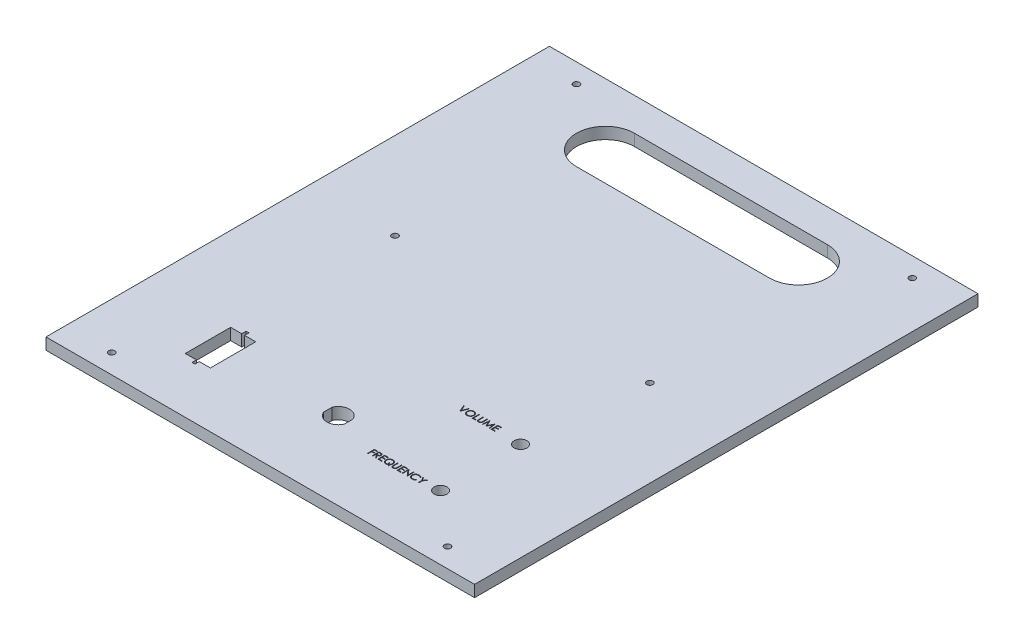
SolidWorks part; units mm, degrees
ref_plane "Front Plane" through (0, 0, 0) normal (0, 0, 1) x (1, 0, 0)
ref_plane "Top Plane" through (0, 0, 0) normal (0, 1, 0) x (1, 0, 0)
ref_plane "Right Plane" through (0, 0, 0) normal (1, 0, 0) x (0, 0, -1)
sketch "Sketch1" plane through (0, 0, 0) normal (0, 1, 0) x (1, 0, 0)
  line L0 (-111, 125.6127) -> (111, 125.6127)
  line L1 (-111, 125.6127) -> (-111, -125.6127)
  line L3 (111, 125.6127) -> (111, -125.6127)
  line L4 (-111, 125.6127) -> (111, -125.6127) construction
  line L5 (-111, -125.6127) -> (111, 125.6127) construction
  line L8 (-111, -125.6127) -> (-111, -165.6127)
  line L9 (-111, -165.6127) -> (111, -165.6127)
  line L10 (111, -125.6127) -> (111, -165.6127)
  point P10 (0, 0)
  dimension "D1" = 222
  dimension "D2" = 40
extrude "Boss-Extrude1" add sketch "Sketch1" along normal blind 6
sketch "Sketch2" plane through (0, 6, 0) normal (0, 1, 0) x (1, 0, 0)
  circle A0 centre (-57, 100.5142) radius 1.6
sketch "Sketch3" plane through (0, 0, 0) normal (0, -1, 0) x (1, 0, 0)
  line L0 (-111, -125.6127) -> (-111, 165.6127) construction
  line L1 (111, -125.6127) -> (-111, -125.6127)
  line L2 (111, -125.6127) -> (111, -95.1873)
  line L3 (111, -95.1873) -> (-111, -95.1873)
  line L4 (-111, -125.6127) -> (-111, -95.1873)
  circle A0 centre (-66, 29.8127) radius 1.6
  circle A1 centre (66, 29.8127) radius 1.6
  dimension "D1" = 3.2
extrude "Cut-Extrude1" cut sketch "Sketch3" against normal blind 10
sketch "Sketch4" plane through (0, 0, 0) normal (0, -1, 0) x (1, 0, 0)
  circle A0 centre (87, 155.6127) radius 1.6
  circle A1 centre (-87, 155.6127) radius 1.6
  circle A2 centre (-87, -85.1873) radius 1.6
  circle A3 centre (87, -85.1873) radius 1.6
extrude "Cut-Extrude2" cut sketch "Sketch4" against normal blind 10
sketch "Sketch5" plane through (0, 0, 0) normal (0, -1, 0) x (-1, 0, 0)
  line L0 (-5.375, -123.0201) -> (-5.375, -127.4052)
  line L1 (5.375, -123.0201) -> (5.375, -127.4052)
  arc A0 (-5.375, -127.4052) -> (5.375, -127.4052) centre (0, -125.2127) ccw
  arc A1 (5.375, -123.0201) -> (-5.375, -123.0201) centre (0, -125.2127) ccw
extrude "Cut-Extrude3" cut sketch "Sketch5" against normal blind 10
sketch "Sketch6" plane through (0, 0, 0) normal (0, -1, 0) x (1, 0, 0)
  circle A0 centre (60.0879, 90.8682) radius 3.3
  circle A1 centre (60.0879, 132.3075) radius 3.3
  point P4 (60.0879, 132.3075)
  dimension "D1" = 6.6
  dimension "D2" = 6.6
extrude "Cut-Extrude4" cut sketch "Sketch6" against normal blind 10
sketch "Sketch10" plane through (0, 6, 0) normal (0, 1, 0) x (1, 0, 0)
  text T0 "VOLUME"
  text T1 "FREQUENCY"
  point P2 (24.2367, -135.0381)
  point P3 (24.0248, -134.4729)
extrude "Cut-Extrude5" cut sketch "Sketch10" against normal blind 1
sketch "Sketch11" plane through (0, 6, 0) normal (0, 1, 0) x (1, 0, 0)
  line L0 (0, 0) -> (0, 95.1873) construction
  line L1 (-111, 95.1873) -> (111, 95.1873) construction
  line L2 (-50, 63.1873) -> (50, 63.1873) construction
  line L3 (-50, 78.1873) -> (50, 78.1873)
  line L4 (-50, 48.1873) -> (50, 48.1873)
  arc A0 (-50, 78.1873) -> (-50, 48.1873) centre (-50, 63.1873) ccw
  arc A1 (50, 48.1873) -> (50, 78.1873) centre (50, 63.1873) ccw
  point P7 (0, 63.1873)
  point P12 (0, 66.3631)
  point P13 (0, 63.1441)
  dimension "D1" = 100
  dimension "D2" = 30
  dimension "D3" = 32
extrude "Cut-Extrude6" cut sketch "Sketch11" against normal blind 10
sketch "Sketch12" plane through (0, 0, 0) normal (0, -1, 0) x (1, 0, 0)
  line L0 (0, 125.2127) -> (-61.0016, 125.2127) construction
  line L2 (-54.5016, 136.9627) -> (-67.5016, 136.9627)
  line L3 (-54.5016, 136.9627) -> (-54.5016, 113.4627)
  line L4 (-54.5016, 113.4627) -> (-67.5016, 113.4627)
  line L5 (-67.5016, 136.9627) -> (-67.5016, 113.4627)
  line L6 (-54.5016, 136.9627) -> (-67.5016, 113.4627) construction
  line L7 (-54.5016, 113.4627) -> (-67.5016, 136.9627) construction
  point P7 (0, 0)
  dimension "D1" = 23.5
  dimension "D2" = 13
  dimension "D3" = 61.0016
extrude "Cut-Extrude7" cut sketch "Sketch12" against normal blind 10
sketch "Sketch13" plane through (0, 0, 0) normal (0, -1, 0) x (1, 0, 0)
  line L0 (-61.0016, 136.9627) -> (-61.0016, 113.4627) construction
  line L1 (-54.5016, 136.9627) -> (-67.5016, 136.9627) construction
  line L2 (-67.5016, 113.4627) -> (-54.5016, 113.4627) construction
  line L4 (-60.2516, 139.2127) -> (-61.7516, 139.2127)
  line L5 (-60.2516, 139.2127) -> (-60.2516, 111.2127)
  line L6 (-60.2516, 111.2127) -> (-61.7516, 111.2127)
  line L7 (-61.7516, 139.2127) -> (-61.7516, 111.2127)
  line L8 (-60.2516, 139.2127) -> (-61.7516, 111.2127) construction
  line L9 (-60.2516, 111.2127) -> (-61.7516, 139.2127) construction
  point P6 (-61.0016, 125.2127)
  dimension "D1" = 28
  dimension "D2" = 1.5
extrude "Cut-Extrude8" cut sketch "Sketch13" against normal blind 10
